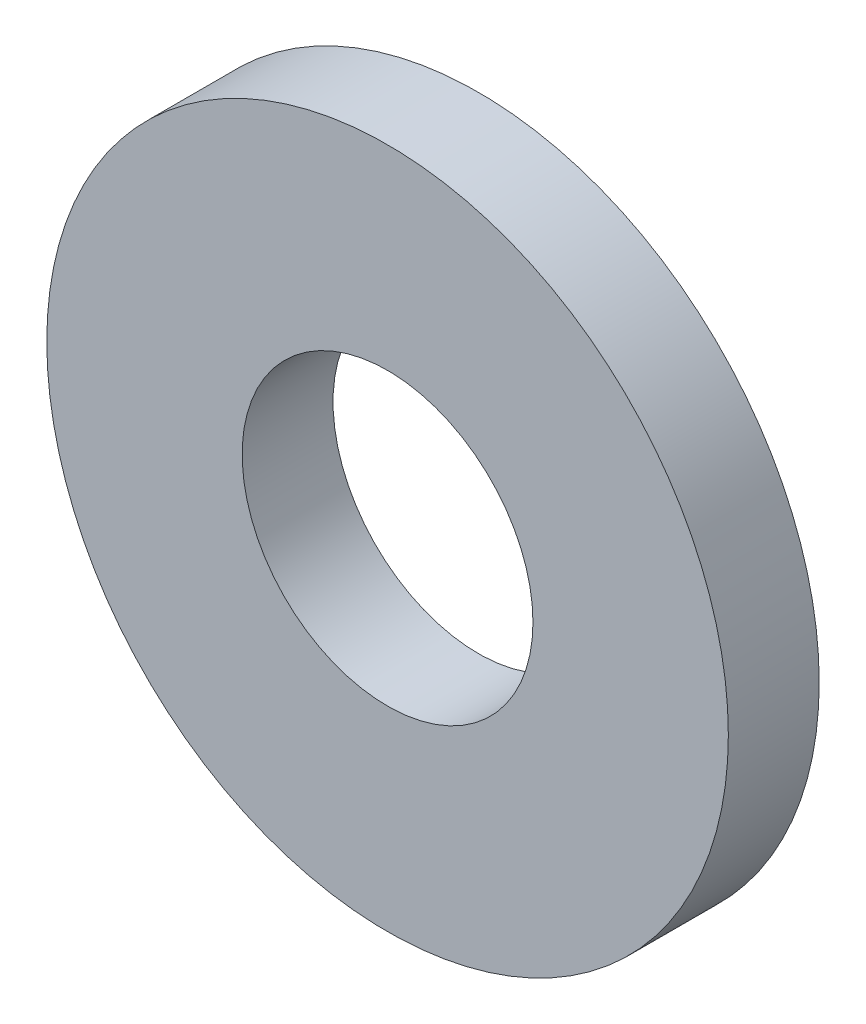
SolidWorks part; units mm, degrees
ref_plane "Front Plane" through (0, 0, 0) normal (1, 0, 0) x (0, 1, 0)
ref_plane "Top Plane" through (0, 0, 0) normal (0, 0, 1) x (0, 1, 0)
ref_plane "Right Plane" through (0, 0, 0) normal (0, 1, 0) x (-1, 0, 0)
sketch "Sketch1" plane through (0, 0, 0) normal (0, 0, 1) x (0, 1, 0)
  circle A0 centre (0, 0) radius 9.525
  dimension "D1" = 19.05
extrude "Boss-Extrude1" add sketch "Sketch1" along normal blind 2.54 contours A0
sketch "Sketch2" plane through (0, 0, 2.54) normal (0, 0, 1) x (1, 0, 0)
  circle A0 centre (0, 0) radius 4.064
  dimension "D1" = 8.128
extrude "Cut-Extrude1" cut sketch "Sketch2" against normal through all
